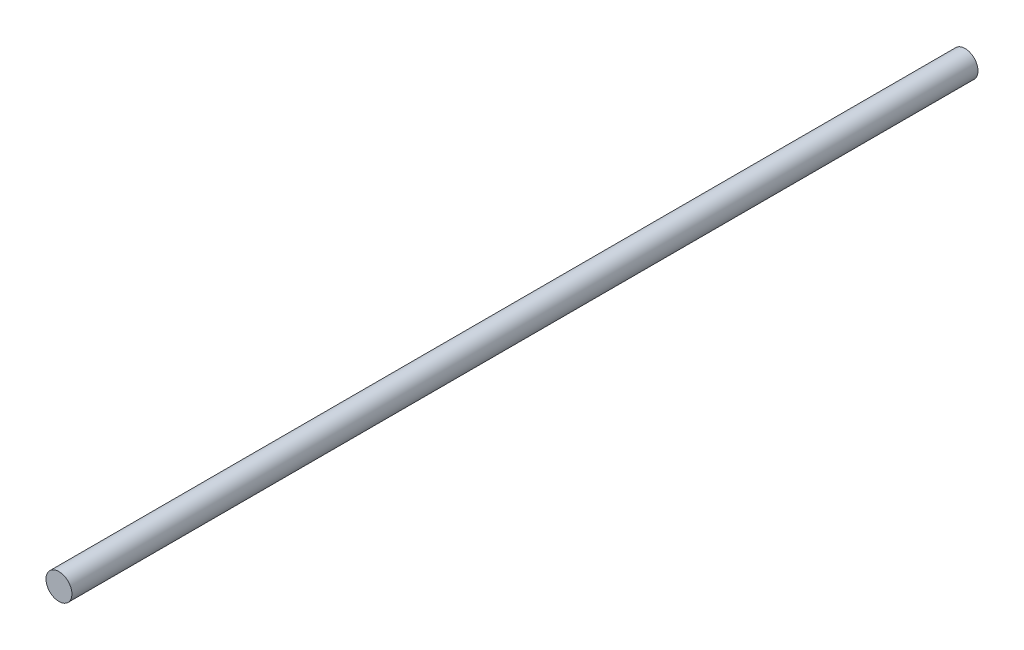
SolidWorks part; units mm, degrees
material "Zinc AC41A Alloy, As Cast"
ref_plane "Front" through (0, 0, 0) normal (0, 0, 1) x (1, 0, 0)
ref_plane "Top" through (0, 0, 0) normal (0, 1, 0) x (1, 0, 0)
ref_plane "Right" through (0, 0, 0) normal (1, 0, 0) x (0, 0, -1)
sketch "Sketch1" plane through (0, 0, 0) normal (0, 0, 1) x (1, 0, 0)
  circle A0 centre (0, 0) radius 0.32
  dimension "D1" = 0.64
extrude "Boss-Extrude1" add sketch "Sketch1" along normal blind 22.352
